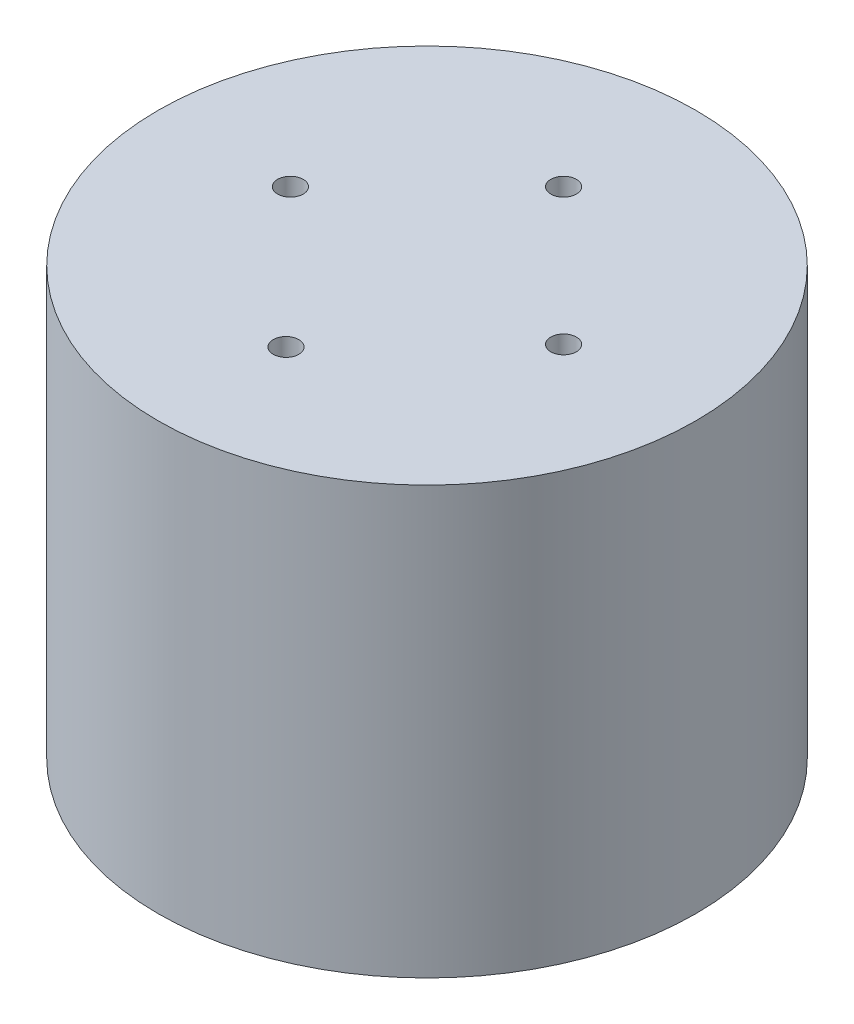
SolidWorks part; units mm, degrees
ref_plane "Plan de face" through (0, 0, 0) normal (0, 0, 1) x (1, 0, 0)
ref_plane "Plan de dessus" through (0, 0, 0) normal (0, 1, 0) x (1, 0, 0)
ref_plane "Plan de droite" through (0, 0, 0) normal (1, 0, 0) x (0, 0, -1)
sketch "Esquisse1" plane through (0, 0, 0) normal (0, 1, 0) x (1, 0, 0)
  circle A0 centre (0, 0) radius 31.5
extrude "Boss.-Extru.1" add sketch "Esquisse1" along normal blind 50
sketch "Esquisse2" plane through (0, 0, 0) normal (0, -1, 0) x (-1, 0, 0)
  circle A0 centre (0, 0) radius 26
extrude "Enlèv. mat.-Extru.1" cut sketch "Esquisse2" against normal blind 20
sketch "Esquisse3" plane through (0, 20, 0) normal (0, -1, 0) x (-1, 0, 0)
  circle A0 centre (0, 0) radius 11
  dimension "D1" = 22
extrude "Enlèv. mat.-Extru.5" cut sketch "Esquisse3" against normal blind 7.5
sketch "Esquisse4" plane through (0, 27.5, 0) normal (0, -1, 0) x (-1, 0, 0)
  circle A0 centre (0, 0) radius 3.25
  dimension "D1" = 6.5
extrude "Enlèv. mat.-Extru.6" cut sketch "Esquisse4" against normal blind 13.5
sketch "Esquisse5" plane through (0, 50, 0) normal (0, 1, 0) x (1, 0, 0)
  line L0 (-26, 0) -> (26, 0)
  line L1 (0, 26) -> (0, -26)
  circle A0 centre (0, 0) radius 26
  point P8 (-16, 0)
  point P9 (0, 16)
  point P10 (16, 0)
  point P11 (0, -16)
  dimension "D1" = 52
sketch "Esquisse11" plane through (0, 50, 0) normal (0, 1, 0) x (1, 0, 0)
  line L0 (0, 26) -> (0, -26) construction
  circle A0 centre (-16, 0) radius 1.5
  circle A1 centre (0, 16) radius 1.5
  circle A2 centre (16, 0) radius 1.5
  circle A3 centre (0, -16.5135) radius 1.5
  point P13 (0, 0)
  dimension "D1" = 3
  dimension "D2" = 3
  dimension "D3" = 3
  dimension "D4" = 3
extrude "Enlèv. mat.-Extru.11" cut sketch "Esquisse11" against normal through all
